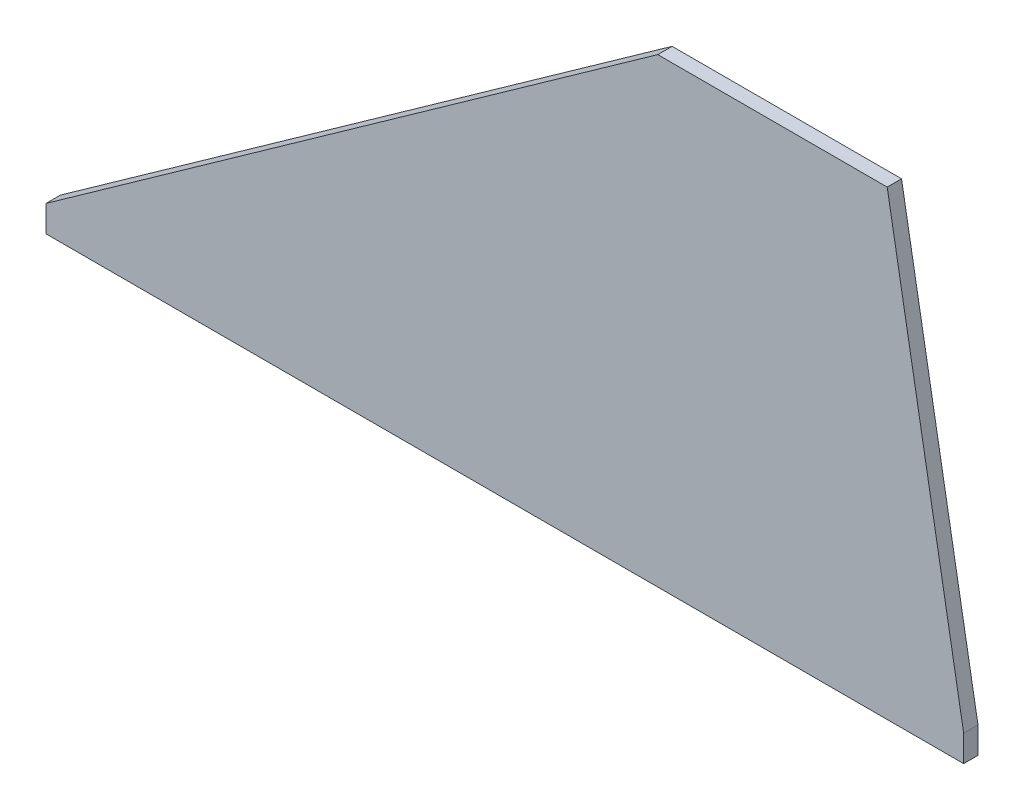
SolidWorks part; units mm, degrees
material "E-Glass Fiber"
ref_plane "Front Plane" through (0, 0, 0) normal (0, 0, 1) x (1, 0, 0)
ref_plane "Top Plane" through (0, 0, 0) normal (0, 1, 0) x (1, 0, 0)
ref_plane "Right Plane" through (0, 0, 0) normal (1, 0, 0) x (0, 0, -1)
sketch "Sketch1" plane through (0, 0, 0) normal (0, 0, 1) x (1, 0, 0)
  line L0 (0, 0) -> (304.8, 0)
  line L1 (55, 0) -> (-55, 0) construction
  line L2 (304.8, 0) -> (304.8, 8.763)
  line L3 (304.8, 8.763) -> (279.4, 153.162)
  line L4 (279.4, 153.162) -> (203.2, 153.162)
  line L5 (203.2, 153.162) -> (0, 8.763)
  line L6 (0, -55) -> (0, 55) construction
  line L7 (0, 8.763) -> (0, 0)
  dimension "D1" = 304.8
  dimension "D2" = 76.2
  dimension "D3" = 153.162
  dimension "D4" = 203.2
  dimension "D5" = 8.763
extrude "Boss-Extrude1" add sketch "Sketch1" along normal mid plane 4.7625
